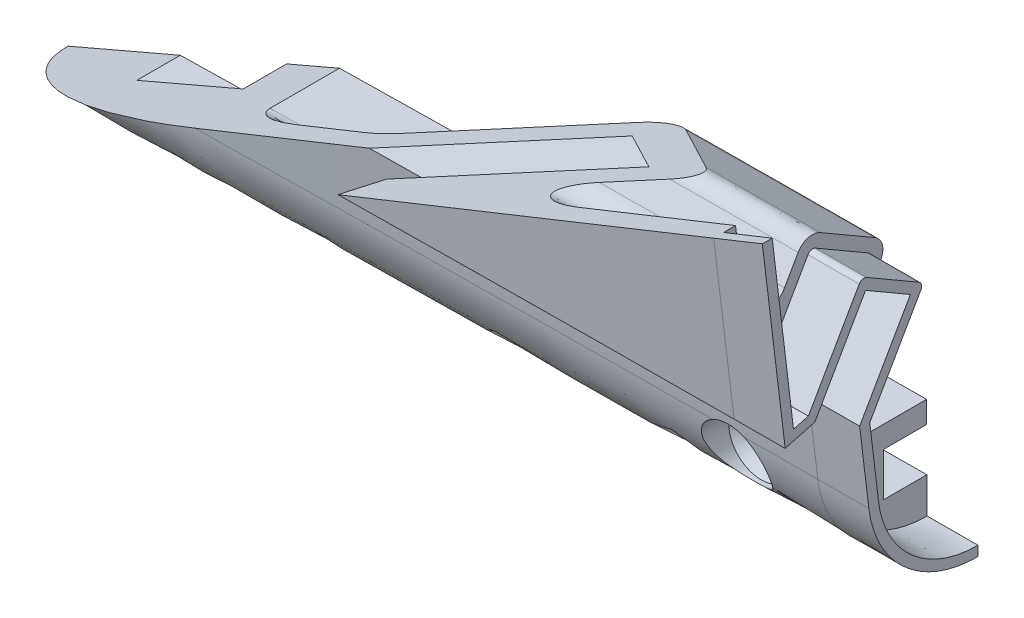
SolidWorks part; units mm, degrees
ref_plane "Front Plane" through (0, 0, 0) normal (0, 0, 1) x (1, 0, 0)
ref_plane "Top Plane" through (0, 0, 0) normal (0, 1, 0) x (1, 0, 0)
ref_plane "Right Plane" through (0, 0, 0) normal (1, 0, 0) x (0, 0, -1)
ref_plane "Plane3" through (-117.056, -3.871, 0) normal (0.9995, 0.0331, 0) x (0, 0, -1)
sketch "Sketch2" plane through (-117.056, -3.871, 0) normal (0.9995, 0.0331, 0) x (0, 0, -1)
  line L0 (-101.6, -41.1511) -> (-101.6, -45.9265)
  line L1 (-101.6, -41.1511) -> (-101.6, -45.9265)
  line L2 (-106.68, -45.9265) -> (-106.68, -50.6257)
  line L3 (-106.68, -45.9265) -> (-106.68, -50.6257)
  line L4 (-101.6, -50.6257) -> (-106.68, -50.6257)
  line L5 (-101.6, -50.6257) -> (-106.68, -50.6257)
  line L6 (-101.6, -50.6257) -> (-101.6, -56.1377)
  line L7 (-101.6, -50.6257) -> (-101.6, -56.1377)
  line L8 (-106.68, -45.9265) -> (-101.6, -45.9265)
  line L9 (-106.68, -45.9265) -> (-101.6, -45.9265)
  line L10 (-106.8705, -50.8162) -> (-108.9961, -53.9781) construction
  line L11 (-101.7905, -43.196) -> (-101.7905, -45.736)
  line L12 (-106.8705, -45.736) -> (-101.7905, -45.736)
  line L13 (-106.8705, -45.736) -> (-106.8705, -50.8162)
  line L14 (-101.7905, -50.8162) -> (-106.8705, -50.8162)
  line L15 (-101.7905, -50.8162) -> (-101.7905, -56.1377)
  line L16 (-101.7905, -43.196) -> (-101.6, -43.196)
  line L17 (-101.7905, -41.1511) -> (-101.7905, -45.736) construction
  line L18 (-120.8053, -33.0481) -> (-115.57, -36.0708)
  line L19 (-120.8053, -33.0481) -> (-115.57, -36.0708)
  line L20 (-109.601, -25.7318) -> (-114.8363, -22.709)
  line L21 (-109.601, -25.7318) -> (-114.8363, -22.709)
  line L22 (-114.8363, -22.709) -> (-120.8053, -33.0481)
  line L23 (-114.8363, -22.709) -> (-120.8053, -33.0481)
  line L24 (-115.57, -36.0708) -> (-109.601, -25.7318)
  line L25 (-115.57, -36.0708) -> (-109.601, -25.7318)
  line L26 (-115.57, -36.0708) -> (-114.523, -44.9291)
  line L28 (-118.1876, -34.5595) -> (-112.2186, -24.2204) construction
  line L29 (-114.6403, -39.5406) -> (-107.0838, -26.4518)
  line L30 (-107.7811, -23.8496) -> (-114.1162, -20.1918)
  line L31 (-116.7185, -20.8891) -> (-124.2749, -33.9778)
  line L33 (-106.1314, -24.8021) -> (-115.766, -19.2393) construction
  line L34 (-115.766, -19.2393) -> (-124.2749, -33.9778) construction
  line L35 (-114.6403, -39.5406) -> (-106.1314, -24.8021) construction
  line L36 (-124.2749, -33.9778) -> (-114.6403, -39.5406) construction
  line L37 (-112.9486, -36.6103) -> (-112.1701, -43.196)
  line L38 (-124.2749, -33.9778) -> (-128.0422, -2.1051)
  line L39 (-128.0422, -2.1051) -> (-132.6063, -0.4439)
  line L40 (-50.8, 0.7495) -> (-2184.4, 0.7495)
  line L41 (-125.822, 0.7495) -> (-133.442, 0.7495)
  line L42 (-122.1519, -30.3004) -> (-125.822, 0.7495)
  arc A0 (-114.523, -44.9291) -> (-101.7905, -56.1377) centre (-101.9108, -43.4383) ccw
  arc A2 (-114.1162, -20.1918) -> (-116.7185, -20.8891) centre (-115.0687, -21.8416) ccw
  arc A3 (-107.0838, -26.4518) -> (-107.7811, -23.8496) centre (-108.7336, -25.4993) ccw
  arc A4 (-133.442, 0.7495) -> (-132.6063, -0.4439) centre (-132.172, 0.7495) ccw
  point P41 (-133.442, 0.7495)
  dimension "D2" = 25.4
  dimension "D6" = 1.905
  dimension "D8" = 2.54
  dimension "D4" = 2.54
  dimension "D5" = 2.54
  dimension "D7" = 2.54
  dimension "D9" = 2.54
  dimension "D10" = 20
  dimension "D11" = 7.62
  dimension "D12" = 3.81
  dimension "D3" = 0.1905
sketch "Sketch3" plane through (0, 0, 101.6) normal (0, 0, 1) x (1, 0, 0)
  arc A0 (622.1039, -83.1998) -> (-622.1039, -83.1998) centre (0, -4954.4862) ccw construction
  arc A1 (622.1039, -83.1998) -> (-622.1039, -83.1998) centre (0, -4954.4862) ccw
sketch "Sketch4" plane through (-117.3306, 4.4304, 1117.6) normal (0.9995, 0.0331, 0) x (0, 0, -1)
  line L29 (1009.8189, -32.1556) -> (1003.4838, -28.4978) construction
  line L32 (1000.8815, -29.1951) -> (993.3251, -42.2838) construction
  line L35 (993.3251, -42.2838) -> (989.5578, -10.4111) construction
  line L50 (995.4481, -38.6064) -> (991.778, -7.5565) construction
  line L51 (1002.03, -44.3768) -> (1003.077, -53.235) construction
  line L52 (1015.8095, -59.1222) -> (1015.8095, -64.4437) construction
  line L53 (1015.8095, -59.1222) -> (1010.7295, -59.1222) construction
  line L54 (1010.7295, -54.042) -> (1010.7295, -59.1222) construction
  line L55 (1010.7295, -54.042) -> (1015.8095, -54.042) construction
  line L56 (1015.8095, -51.502) -> (1015.8095, -54.042) construction
  line L57 (1015.8095, -51.502) -> (1016, -51.502) construction
  line L58 (1004.6514, -44.9163) -> (1005.4299, -51.502) construction
  line L60 (1002.7637, -31.015) -> (996.7947, -41.3541) construction
  line L61 (1007.999, -34.0377) -> (1002.7637, -31.015) construction
  line L62 (1002.03, -44.3768) -> (1007.999, -34.0377) construction
  line L64 (991.5295, -5.4538) -> (988.9718, -5.4538)
  line L69 (1009.8189, -32.1556) -> (1003.4838, -28.4978)
  line L70 (1000.8815, -29.1951) -> (999.2724, -31.9822)
  line L71 (993.3251, -42.2838) -> (988.9718, -5.4538)
  line L74 (994.5502, -31.0104) -> (991.5295, -5.4538)
  line L75 (1002.03, -44.3768) -> (1003.077, -53.235)
  line L76 (1015.8095, -59.1222) -> (1015.8095, -64.4437)
  line L77 (1015.8095, -59.1222) -> (1010.7295, -59.1222)
  line L78 (1010.7295, -54.042) -> (1010.7295, -59.1222)
  line L79 (1010.7295, -54.042) -> (1015.8095, -54.042)
  line L80 (1015.8095, -51.502) -> (1015.8095, -54.042)
  line L81 (1015.8095, -51.502) -> (1007.6873, -51.502)
  line L82 (1004.7505, -45.7539) -> (1005.1649, -49.2601)
  line L84 (1002.7637, -31.015) -> (996.7947, -41.3541)
  line L85 (1007.999, -34.0377) -> (1002.7637, -31.015)
  line L86 (1002.03, -44.3768) -> (1007.999, -34.0377)
  line L87 (996.7947, -41.3541) -> (993.3251, -42.2838)
  line L88 (1005.0732, -44.1858) -> (1010.5162, -34.7578)
  arc A8 (1010.5162, -34.7578) -> (1009.8189, -32.1556) centre (1008.8664, -33.8053) ccw construction
  arc A9 (1003.4838, -28.4978) -> (1000.8815, -29.1951) centre (1002.5313, -30.1476) ccw construction
  arc A11 (1003.077, -53.235) -> (1015.8095, -64.4437) centre (1015.6892, -51.7443) ccw construction
  arc A12 (1010.5162, -34.7578) -> (1009.8189, -32.1556) centre (1008.8664, -33.8053) ccw
  arc A13 (1003.4838, -28.4978) -> (1000.8815, -29.1951) centre (1002.5313, -30.1476) ccw
  arc A15 (1003.077, -53.235) -> (1015.8095, -64.4437) centre (1015.6892, -51.7443) ccw
  arc A16 (1005.1649, -49.2601) -> (1007.6873, -51.502) centre (1007.6873, -48.962) ccw
  arc A17 (1004.7505, -45.7539) -> (1005.0732, -44.1858) centre (1007.2729, -45.4558) cw
  arc A18 (994.5502, -31.0104) -> (999.2724, -31.9822) centre (997.0727, -30.7122) ccw
  dimension "D2" = 2.54
  dimension "D1" = 36.83
sweep "Sweep3" add profiles "Sketch4" path "Sketch3"
sketch "Sketch5" plane through (0, 0, 101.7905) normal (0, 0, -1) x (-1, 0, 0)
  line L0 (211.6509, -4.1577) -> (0, -4954.4862) construction
  line L1 (0, -4954.4862) -> (22.6652, -1.2703) construction
  line L2 (117.0808, -1.0187) -> (0, -4954.4862) construction
  arc A1 (628.0925, -39.606) -> (-627.2635, -39.5001) centre (0, -4954.4862) ccw construction
  point P16 (117.0808, -1.0187)
ref_plane "Plane1" through (-211.4422, -9.0402, 0) normal (-0.9991, -0.0427, 0) x (0.0427, -0.9991, 0)
ref_plane "Plane2" through (-22.6706, -0.1037, 0) normal (1, 0.0046, 0) x (-0.0046, 1, 0)
other "SurfaceCut1"
other "SurfaceCut2"
sketch "Sketch8" plane through (-117.056, -3.871, 0) normal (0.9995, 0.0331, 0) x (0, 0, -1)
  line L0 (-106.8705, -50.8162) -> (-106.8705, -45.736)
  line L1 (-106.8705, -50.8162) -> (-106.8705, -45.736)
  line L2 (-106.8705, -48.2761) -> (-119.5705, -48.2761)
  line L3 (-119.5705, -48.2761) -> (-119.5705, -44.4661)
  line L4 (-119.5705, -44.4661) -> (-110.6805, -44.4661)
  line L5 (-110.6805, -44.4661) -> (-108.7755, -46.3711)
  line L6 (-108.7755, -46.3711) -> (-106.8705, -46.3711)
  line L7 (-119.5705, -48.2761) -> (-117.7248, -48.2761) construction
  dimension "D1" = 1.905
  dimension "D2" = 1.905
  dimension "D3" = 12.7
  dimension "D4" = 45
  dimension "D5" = 3.81
revolve "Cut-Revolve1" cut sketch "Sketch8" angle 360 about L7
sketch "Sketch9" plane through (0, 0, 106.8705) normal (0, 0, -1) x (-1, 0, 0)
  line L0 (198.0737, -52.2212) -> (197.8686, -57.297) construction
  line L1 (32.934, -48.3318) -> (32.8999, -53.4117) construction
  arc A1 (209.5755, -52.6994) -> (22.4502, -48.2726) centre (0, -4954.4862) ccw construction
  arc A2 (209.3585, -57.7748) -> (22.4269, -53.3526) centre (0, -4954.4862) ccw construction
  point P8 (197.9712, -54.7591)
  point P11 (0, -4954.4862)
  point P16 (115.4604, -52.1207)
  dimension "D1" = 82.55
  dimension "D2" = 82.55
sketch "Sketch10" plane through (0, 0, 106.8705) normal (0, 0, -1) x (-1, 0, 0)
  line L0 (32.934, -48.3318) -> (32.8999, -53.4117) construction
  point P0 (32.917, -50.8717)
  point P1 (197.9712, -54.7591)
pattern_sketch "Sketch-Pattern1" of "Cut-Revolve1" driven by "Sketch10"
sketch "Sketch12" plane through (0, 0, 101.7905) normal (0, 0, -1) x (-1, 0, 0)
  line L0 (22.4618, -45.7328) -> (0, -4954.4862) construction
  line L1 (0, -4954.4862) -> (16.4928, -45.7091) construction
  arc A1 (209.684, -50.1619) -> (22.4618, -45.7328) centre (0, -4954.4862) ccw construction
  arc A2 (22.4618, -45.7328) -> (16.4928, -45.7091) centre (0, -4954.4862) ccw
  dimension "D1" = 5.969
sketch "Sketch11" plane through (-22.6706, -0.1037, 0) normal (1, 0.0046, 0) x (0, 0, -1)
  line L0 (-127.4772, 0.4166) -> (-123.2949, -34.9658)
  line L1 (-123.2949, -34.9658) -> (-121.5584, -34.5006)
  line L2 (-121.5584, -34.5006) -> (-115.5722, -24.132)
  line L3 (-114.7047, -23.8996) -> (-108.5896, -27.4302)
  line L4 (-108.3571, -28.2976) -> (-114.3903, -38.7475)
  line L5 (-114.3903, -38.7475) -> (-113.3879, -47.2283)
  line L6 (-127.4931, 0.5508) -> (-123.2949, -34.9658) construction
  line L7 (-101.7905, -58.5707) -> (-101.7905, -57.4277)
  line L8 (-101.7905, -53.2494) -> (-101.7905, -58.5707) construction
  line L9 (-101.7905, -57.4277) -> (-101.8013, -57.4277)
  line L10 (-115.2547, -23.5821) -> (-108.0396, -27.7477) construction
  line L11 (-108.0396, -27.7477) -> (-114.3903, -38.7475) construction
  line L12 (-121.5584, -34.5006) -> (-115.2547, -23.5821) construction
  line L18 (-126.0705, 0.4166) -> (-128.6282, 0.4166)
  line L19 (-128.6282, 0.4166) -> (-124.2749, -36.4117)
  line L20 (-124.2749, -36.4117) -> (-120.8053, -35.4821)
  line L21 (-120.8053, -35.4821) -> (-114.8363, -25.1435)
  line L22 (-114.8363, -25.1435) -> (-109.601, -28.1661)
  line L23 (-109.601, -28.1661) -> (-115.57, -38.5047)
  line L24 (-115.57, -38.5047) -> (-114.523, -47.3625)
  line L25 (-101.7905, -58.5707) -> (-101.7905, -53.2494)
  line L26 (-101.7905, -53.2494) -> (-106.8705, -53.2494)
  line L27 (-106.8705, -53.2494) -> (-106.8705, -48.1694)
  line L28 (-106.8705, -48.1694) -> (-101.7905, -48.1694)
  line L29 (-101.7905, -48.1694) -> (-101.7905, -45.6295)
  line L30 (-101.7905, -45.6295) -> (-109.9127, -45.6295)
  line L31 (-112.4351, -43.3877) -> (-112.8495, -39.8818)
  line L32 (-112.5268, -38.3137) -> (-107.0838, -28.8861)
  line L33 (-107.781, -26.284) -> (-114.1162, -22.6264)
  line L34 (-116.7185, -23.3237) -> (-118.3276, -26.1106)
  line L35 (-123.0498, -25.1389) -> (-126.0705, 0.4166)
  line L36 (-127.4772, 0.4166) -> (-128.6282, 0.4166)
  line L37 (-128.6282, 0.4166) -> (-124.2749, -36.4117)
  line L38 (-124.2749, -36.4117) -> (-120.8053, -35.4821)
  line L39 (-120.8053, -35.4821) -> (-114.8363, -25.1435)
  line L40 (-114.8363, -25.1435) -> (-109.601, -28.1661)
  line L41 (-109.601, -28.1661) -> (-115.57, -38.5047)
  line L42 (-115.57, -38.5047) -> (-114.523, -47.3625)
  arc A0 (-108.5896, -27.4302) -> (-108.3571, -28.2976) centre (-108.9071, -27.9801) cw
  arc A1 (-115.5722, -24.132) -> (-114.7047, -23.8996) centre (-115.0222, -24.4495) cw
  arc A4 (-112.4351, -43.3877) -> (-109.9127, -45.6295) centre (-109.9127, -43.0896) ccw
  arc A5 (-112.5268, -38.3137) -> (-112.8495, -39.8818) centre (-110.3273, -39.5836) ccw
  arc A6 (-107.0838, -28.8861) -> (-107.781, -26.284) centre (-108.7335, -27.9337) ccw
  arc A7 (-114.1162, -22.6264) -> (-116.7185, -23.3237) centre (-115.0687, -24.2762) ccw
  spline S0 degree 1 poles (-113.3879, -47.2283) (-101.8013, -57.4277) knots 0 0 1 1 construction
  spline S1 degree 3 poles (-113.3879, -47.2283) (-113.3048, -47.9312) (-113.0054, -49.3311) (-111.9316, -51.9219) (-109.7159, -54.7453) (-106.0351, -56.9462) (-103.2019, -57.441) (-101.8013, -57.4277) knots 0 0 0 0 0.125 0.25 0.5 0.75 1 1 1 1
  spline S2 degree 3 poles (1806.7112, 500.6593) (415.3182, 185.4237) (-128.7728, 19.3055) (-114.2511, -48.8979) (-114.1523, -49.2753) (-113.8076, -50.3831) (-113.513, -51.0943) (-112.7943, -52.462) (-112.3662, -53.122) (-111.4114, -54.3345) (-110.8822, -54.8938) (-110.0099, -55.6614) (-109.7043, -55.9064) (-109.0766, -56.3638) (-108.7542, -56.5768) (-107.762, -57.1694) (-107.0674, -57.5033) (-105.9744, -57.9099) (-105.6018, -58.0293) (-104.8546, -58.2314) (-104.4782, -58.315) (-51.6561, -67.5542) (53.4105, 250.9973) (369.459, 1883.4824) knots -11.048432 -11.048432 -11.048432 -11.048432 0.0625 0.0625 0.125 0.125 0.25 0.25 0.375 0.375 0.5 0.5 0.5625 0.5625 0.625 0.625 0.75 0.75 0.8125 0.8125 0.875 0.875 9.519326 9.519326 9.519326 9.519326 only from (-114.523, -47.3625) to (-101.7905, -58.5707)
  spline S3 degree 3 poles (-966.8365, -555.2861) (-146.5253, 43.3444) (-110.7563, -19.4508) (-119.0219, -26.9033) (-119.2485, -27.051) (-119.7291, -27.2663) (-119.9898, -27.337) (-120.3827, -27.3799) (-120.5144, -27.384) (-120.779, -27.3716) (-120.9121, -27.3548) (-121.1705, -27.3014) (-121.297, -27.2648) (-121.5443, -27.1719) (-121.6661, -27.1149) (-121.896, -26.9844) (-122.0051, -26.9107) (-122.2115, -26.7465) (-122.3097, -26.6551) (-122.5785, -26.3621) (-122.7254, -26.141) (-131.5662, -6.8587) (104.7841, 84.3424) (817.0786, 315.6789) knots -5.03449 -5.03449 -5.03449 -5.03449 0.125 0.125 0.25 0.25 0.375 0.375 0.4375 0.4375 0.5 0.5 0.5625 0.5625 0.625 0.625 0.6875 0.6875 0.75 0.75 0.875 0.875 10.718854 10.718854 10.718854 10.718854 only from (-118.3276, -26.1106) to (-123.0498, -25.1389)
  spline S4 degree 3 poles (-114.523, -47.3625) (-114.4771, -47.7503) (-114.4136, -48.1349) (-114.2511, -48.8979) (-114.1523, -49.2753) (-113.8076, -50.3831) (-113.513, -51.0943) (-112.7943, -52.462) (-112.3662, -53.122) (-111.4114, -54.3345) (-110.8822, -54.8938) (-110.0099, -55.6614) (-109.7043, -55.9064) (-109.0766, -56.3638) (-108.7542, -56.5768) (-107.762, -57.1694) (-107.0674, -57.5033) (-105.9744, -57.9099) (-105.6018, -58.0293) (-104.8546, -58.2314) (-104.4782, -58.315) (-103.3407, -58.514) (-102.5713, -58.5781) (-101.7905, -58.5707) knots 0 0 0 0 0.0625 0.0625 0.125 0.125 0.25 0.25 0.375 0.375 0.5 0.5 0.5625 0.5625 0.625 0.625 0.75 0.75 0.8125 0.8125 0.875 0.875 1 1 1 1
  dimension "D3" = 0.635
  dimension "D1" = 0
  dimension "D2" = 1.143
sweep "Sweep4" add profiles "Sketch11" path "Sketch12"
sketch "Sketch14" plane through (-211.4422, -9.0402, 0) normal (-0.9991, -0.0427, 0) x (0, 0, 1)
  line L0 (113.0095, -42.7133) -> (113.9971, -34.3581)
  line L1 (113.9971, -34.3581) -> (107.5192, -23.138)
  line L2 (107.5192, -23.138) -> (115.3941, -18.5914)
  line L3 (115.3941, -18.5914) -> (121.8095, -29.7031)
  line L4 (121.8095, -29.7031) -> (122.9682, -30.0136)
  line L5 (122.9682, -30.0136) -> (127.1147, 5.0658)
  line L18 (128.6282, 4.8869) -> (126.0705, 4.8869)
  line L19 (126.0705, 4.8869) -> (123.0498, -20.6686)
  line L20 (118.3276, -21.6403) -> (116.7185, -18.8534)
  line L21 (114.1162, -18.1561) -> (107.7811, -21.8137)
  line L22 (107.0838, -24.4158) -> (112.5268, -33.8434)
  line L23 (112.8495, -35.4115) -> (112.4351, -38.9175)
  line L24 (109.9127, -41.1592) -> (101.7905, -41.1592)
  line L25 (101.7905, -41.1592) -> (101.7905, -43.6991)
  line L26 (101.7905, -43.6991) -> (106.8705, -43.6991)
  line L27 (106.8705, -43.6991) -> (106.8705, -48.7791)
  line L28 (106.8705, -48.7791) -> (101.7905, -48.7791)
  line L29 (101.7905, -48.7791) -> (101.7905, -54.1004)
  line L30 (114.523, -42.8922) -> (115.57, -34.0344)
  line L31 (115.57, -34.0344) -> (109.601, -23.6958)
  line L32 (109.601, -23.6958) -> (114.8363, -20.6732)
  line L33 (114.8363, -20.6732) -> (120.8053, -31.0118)
  line L34 (120.8053, -31.0118) -> (124.2749, -31.9414)
  line L35 (124.2749, -31.9414) -> (128.6282, 4.8869)
  line L36 (128.6282, 4.8869) -> (126.0705, 4.8869)
  line L37 (126.0705, 4.8869) -> (123.0498, -20.6686)
  line L38 (118.3276, -21.6403) -> (116.7185, -18.8534)
  line L39 (114.1162, -18.1561) -> (107.7811, -21.8137)
  line L40 (107.0838, -24.4158) -> (112.5268, -33.8434)
  line L41 (112.8495, -35.4115) -> (112.4351, -38.9175)
  line L42 (109.9127, -41.1592) -> (101.7905, -41.1592)
  line L43 (101.7905, -41.1592) -> (101.7905, -43.6991)
  line L44 (101.7905, -43.6991) -> (106.8705, -43.6991)
  line L45 (106.8705, -43.6991) -> (106.8705, -48.7791)
  line L46 (106.8705, -48.7791) -> (101.7905, -48.7791)
  line L47 (101.7905, -48.7791) -> (101.7905, -54.1004)
  line L48 (114.523, -42.8922) -> (115.57, -34.0344)
  line L49 (115.57, -34.0344) -> (109.601, -23.6958)
  line L50 (109.601, -23.6958) -> (114.8363, -20.6732)
  line L51 (114.8363, -20.6732) -> (120.8053, -31.0118)
  line L52 (120.8053, -31.0118) -> (124.2749, -31.9414)
  line L53 (124.2749, -31.9414) -> (128.6282, 4.8869)
  arc A4 (116.7185, -18.8534) -> (114.1162, -18.1561) centre (115.0687, -19.8059) ccw
  arc A5 (107.7811, -21.8137) -> (107.0838, -24.4158) centre (108.7335, -23.4634) ccw
  arc A6 (112.8495, -35.4115) -> (112.5268, -33.8434) centre (110.3273, -35.1133) ccw
  arc A7 (109.9127, -41.1592) -> (112.4351, -38.9175) centre (109.9127, -38.6193) ccw
  arc A8 (116.7185, -18.8534) -> (114.1162, -18.1561) centre (115.0687, -19.8059) ccw
  arc A9 (107.7811, -21.8137) -> (107.0838, -24.4158) centre (108.7335, -23.4634) ccw
  arc A10 (112.8495, -35.4115) -> (112.5268, -33.8434) centre (110.3273, -35.1133) ccw
  arc A11 (109.9127, -41.1592) -> (112.4351, -38.9175) centre (109.9127, -38.6193) ccw
  spline S0 degree 1 poles (101.8049, -52.5765) (113.0095, -42.7133) knots 0 0 1 1 construction
  spline S1 degree 3 poles (101.8049, -52.5765) (102.4893, -52.583) (103.8689, -52.4674) (106.4858, -51.7551) (109.4658, -49.9761) (112.0284, -46.7154) (112.8505, -44.0584) (113.0095, -42.7133) knots 0 0 0 0 0.125 0.25 0.5 0.75 1 1 1 1
  spline S2 degree 3 poles (-1420.2451, -2589.1907) (7.5348, 76.4537) (129.3579, -7.252) (122.7249, -21.671) (122.575, -21.8961) (122.2185, -22.2837) (122.0069, -22.4517) (121.6628, -22.6462) (121.5435, -22.702) (121.2955, -22.795) (121.1665, -22.8321) (120.908, -22.8851) (120.7774, -22.9014) (120.5134, -22.9137) (120.3791, -22.9094) (120.1163, -22.8803) (119.987, -22.8557) (119.7325, -22.7864) (119.6063, -22.7412) (119.2436, -22.578) (119.0214, -22.433) (93.7379, 0.421) (581.1886, 448.0858) (2362.312, 1968.4478) knots -7.286241 -7.286241 -7.286241 -7.286241 0.125 0.125 0.25 0.25 0.375 0.375 0.4375 0.4375 0.5 0.5 0.5625 0.5625 0.625 0.625 0.6875 0.6875 0.75 0.75 0.875 0.875 16.766809 16.766809 16.766809 16.766809 only from (123.0498, -20.6686) to (118.3276, -21.6403)
  spline S3 degree 3 poles (-288.3388, 2916.9987) (-102.777, 757.3692) (19.5454, -60.9671) (103.3479, -54.0254) (103.7348, -53.9753) (104.8774, -53.7738) (105.6202, -53.5717) (107.068, -53.0324) (107.777, -52.6914) (109.1008, -51.8981) (109.7227, -51.4442) (110.5948, -50.6762) (110.8766, -50.4042) (111.4099, -49.8396) (111.662, -49.5468) (112.3757, -48.6378) (112.795, -47.9912) (113.3369, -46.9586) (113.5026, -46.6041) (113.7979, -45.8886) (113.9285, -45.5258) (132.5439, 14.5864) (-288.4354, 203.7302) (-2703.1014, 979.8882) knots -13.349036 -13.349036 -13.349036 -13.349036 0.0625 0.0625 0.125 0.125 0.25 0.25 0.375 0.375 0.5 0.5 0.5625 0.5625 0.625 0.625 0.75 0.75 0.8125 0.8125 0.875 0.875 11.030088 11.030088 11.030088 11.030088 only from (101.7905, -54.1004) to (114.523, -42.8922)
  spline S4 degree 3 poles (123.0498, -20.6686) (123.0184, -20.9338) (122.9449, -21.1927) (122.7249, -21.671) (122.575, -21.8961) (122.2185, -22.2837) (122.0069, -22.4517) (121.6628, -22.6462) (121.5435, -22.702) (121.2955, -22.795) (121.1665, -22.8321) (120.908, -22.8851) (120.7774, -22.9014) (120.5134, -22.9137) (120.3791, -22.9094) (120.1163, -22.8803) (119.987, -22.8557) (119.7325, -22.7864) (119.6063, -22.7412) (119.2436, -22.578) (119.0214, -22.433) (118.6267, -22.0763) (118.4611, -21.8716) (118.3276, -21.6403) knots 0 0 0 0 0.125 0.125 0.25 0.25 0.375 0.375 0.4375 0.4375 0.5 0.5 0.5625 0.5625 0.625 0.625 0.6875 0.6875 0.75 0.75 0.875 0.875 1 1 1 1
  spline S5 degree 3 poles (101.7905, -54.1004) (102.1809, -54.1041) (102.5705, -54.0898) (103.3479, -54.0254) (103.7348, -53.9753) (104.8774, -53.7738) (105.6202, -53.5717) (107.068, -53.0324) (107.777, -52.6914) (109.1008, -51.8981) (109.7227, -51.4442) (110.5948, -50.6762) (110.8766, -50.4042) (111.4099, -49.8396) (111.662, -49.5468) (112.3757, -48.6378) (112.795, -47.9912) (113.3369, -46.9586) (113.5026, -46.6041) (113.7979, -45.8886) (113.9285, -45.5258) (114.2702, -44.4227) (114.4313, -43.6677) (114.523, -42.8922) knots 0 0 0 0 0.0625 0.0625 0.125 0.125 0.25 0.25 0.375 0.375 0.5 0.5 0.5625 0.5625 0.625 0.625 0.75 0.75 0.8125 0.8125 0.875 0.875 1 1 1 1
  dimension "D1" = 0
  dimension "D2" = 1.524
sketch "Sketch15" plane through (-211.4422, -9.0402, 0) normal (-0.9991, -0.0427, 0) x (0, 0, 1)
  line L0 (113.0095, -42.7133) -> (113.9971, -34.3581) construction
  line L1 (113.9971, -34.3581) -> (107.5192, -23.138) construction
  line L2 (107.5192, -23.138) -> (115.3941, -18.5914) construction
  line L3 (115.3941, -18.5914) -> (121.8095, -29.7031) construction
  line L4 (121.8095, -29.7031) -> (122.9682, -30.0136) construction
  line L5 (122.9682, -30.0136) -> (127.1147, 5.0658) construction
  line L6 (113.0095, -42.7133) -> (113.9724, -34.5675)
  line L7 (113.8917, -34.1755) -> (107.5192, -23.138)
  line L8 (107.5192, -23.138) -> (115.3941, -18.5914)
  line L9 (115.3941, -18.5914) -> (121.678, -29.4753)
  line L10 (122.0636, -29.7712) -> (122.2594, -29.8237)
  line L11 (123.0543, -29.2848) -> (127.0936, 4.8869)
  line L12 (101.7905, -48.7791) -> (101.7905, -54.1004) construction
  line L13 (101.7905, -48.7791) -> (101.7905, -52.5765)
  line L14 (101.8049, -52.5765) -> (101.7905, -52.5765)
  line L18 (124.2749, -31.9414) -> (128.6282, 4.8869)
  line L19 (128.6282, 4.8869) -> (126.0705, 4.8869)
  line L20 (126.0705, 4.8869) -> (123.0498, -20.6686)
  line L21 (118.3276, -21.6403) -> (116.7185, -18.8534)
  line L22 (114.1162, -18.1561) -> (107.7811, -21.8137)
  line L23 (107.0838, -24.4158) -> (112.5268, -33.8434)
  line L24 (112.8495, -35.4115) -> (112.4351, -38.9175)
  line L25 (109.9127, -41.1592) -> (101.7905, -41.1592)
  line L26 (101.7905, -41.1592) -> (101.7905, -43.6991)
  line L27 (101.7905, -43.6991) -> (106.8705, -43.6991)
  line L28 (106.8705, -43.6991) -> (106.8705, -48.7791)
  line L29 (106.8705, -48.7791) -> (101.7905, -48.7791)
  line L30 (101.7905, -48.7791) -> (101.7905, -54.1004)
  line L31 (114.523, -42.8922) -> (115.57, -34.0344)
  line L32 (115.57, -34.0344) -> (109.601, -23.6958)
  line L33 (109.601, -23.6958) -> (114.8363, -20.6732)
  line L34 (114.8363, -20.6732) -> (120.8053, -31.0118)
  line L35 (120.8053, -31.0118) -> (124.2749, -31.9414)
  line L37 (127.0936, 4.8869) -> (126.0705, 4.8869)
  line L38 (126.0705, 4.8869) -> (123.0498, -20.6686)
  line L39 (118.3276, -21.6403) -> (116.7185, -18.8534)
  line L40 (114.1162, -18.1561) -> (107.7811, -21.8137)
  line L41 (107.0838, -24.4158) -> (112.5268, -33.8434)
  line L42 (112.8495, -35.4115) -> (112.4351, -38.9175)
  line L43 (109.9127, -41.1592) -> (101.7905, -41.1592)
  line L44 (101.7905, -41.1592) -> (101.7905, -43.6991)
  line L45 (101.7905, -43.6991) -> (106.8705, -43.6991)
  line L46 (106.8705, -43.6991) -> (106.8705, -48.7791)
  line L47 (106.8705, -48.7791) -> (101.7905, -48.7791)
  arc A0 (113.9724, -34.5675) -> (113.8917, -34.1755) centre (113.3418, -34.493) ccw
  arc A1 (121.678, -29.4753) -> (122.0636, -29.7712) centre (122.2279, -29.1578) ccw
  arc A2 (122.2594, -29.8237) -> (123.0543, -29.2848) centre (122.4237, -29.2103) ccw
  arc A4 (116.7185, -18.8534) -> (114.1162, -18.1561) centre (115.0687, -19.8059) ccw
  arc A5 (107.7811, -21.8137) -> (107.0838, -24.4158) centre (108.7335, -23.4634) ccw
  arc A6 (112.8495, -35.4115) -> (112.5268, -33.8434) centre (110.3273, -35.1133) ccw
  arc A7 (109.9127, -41.1592) -> (112.4351, -38.9175) centre (109.9127, -38.6193) ccw
  arc A8 (116.7185, -18.8534) -> (114.1162, -18.1561) centre (115.0687, -19.8059) ccw
  arc A9 (107.7811, -21.8137) -> (107.0838, -24.4158) centre (108.7335, -23.4634) ccw
  arc A10 (112.8495, -35.4115) -> (112.5268, -33.8434) centre (110.3273, -35.1133) ccw
  arc A11 (109.9127, -41.1592) -> (112.4351, -38.9175) centre (109.9127, -38.6193) ccw
  spline S0 degree 3 poles (1969.6766, 654.3437) (8.5109, 56.766) (75.3403, -60.2329) (106.4858, -51.7551) (109.4658, -49.9761) (134.2797, -18.4018) (-16.091, 107.1074) (-926.156, -1745.3361) knots -5.450838 -5.450838 -5.450838 -5.450838 0.125 0.25 0.5 0.75 7.512309 7.512309 7.512309 7.512309 only from (101.8049, -52.5765) to (113.0095, -42.7133) construction
  spline S1 degree 3 poles (101.8049, -52.5765) (102.4893, -52.583) (103.8689, -52.4674) (106.4858, -51.7551) (109.4658, -49.9761) (112.0284, -46.7154) (112.8505, -44.0584) (113.0095, -42.7133) knots 0 0 0 0 0.125 0.25 0.5 0.75 1 1 1 1
  spline S2 degree 3 poles (-1420.2451, -2589.1907) (7.5348, 76.4537) (129.3579, -7.252) (122.7249, -21.671) (122.575, -21.8961) (122.2185, -22.2837) (122.0069, -22.4517) (121.6628, -22.6462) (121.5435, -22.702) (121.2955, -22.795) (121.1665, -22.8321) (120.908, -22.8851) (120.7774, -22.9014) (120.5134, -22.9137) (120.3791, -22.9094) (120.1163, -22.8803) (119.987, -22.8557) (119.7325, -22.7864) (119.6063, -22.7412) (119.2436, -22.578) (119.0214, -22.433) (93.7379, 0.421) (581.1886, 448.0858) (2362.312, 1968.4478) knots -7.286241 -7.286241 -7.286241 -7.286241 0.125 0.125 0.25 0.25 0.375 0.375 0.4375 0.4375 0.5 0.5 0.5625 0.5625 0.625 0.625 0.6875 0.6875 0.75 0.75 0.875 0.875 16.766809 16.766809 16.766809 16.766809 only from (123.0498, -20.6686) to (118.3276, -21.6403)
  spline S3 degree 3 poles (-93.3253, 926.6784) (-10.5613, 232.0775) (53.1389, -58.1844) (103.3479, -54.0254) (103.7348, -53.9753) (104.8774, -53.7738) (105.6202, -53.5717) (107.068, -53.0324) (107.777, -52.6914) (109.1008, -51.8981) (109.7227, -51.4442) (110.5948, -50.6762) (110.8766, -50.4042) (111.4099, -49.8396) (111.662, -49.5468) (112.3757, -48.6378) (112.795, -47.9912) (113.3369, -46.9586) (113.5026, -46.6041) (113.7979, -45.8886) (113.9285, -45.5258) (125.9187, -6.8076) (-43.2917, 84.8615) (-804.6708, 350.8867) knots -7.947776 -7.947776 -7.947776 -7.947776 0.0625 0.0625 0.125 0.125 0.25 0.25 0.375 0.375 0.5 0.5 0.5625 0.5625 0.625 0.625 0.75 0.75 0.8125 0.8125 0.875 0.875 7.39364 7.39364 7.39364 7.39364 only from (101.7905, -54.1004) to (114.523, -42.8922)
  spline S4 degree 3 poles (123.0498, -20.6686) (123.0184, -20.9338) (122.9449, -21.1927) (122.7249, -21.671) (122.575, -21.8961) (122.2185, -22.2837) (122.0069, -22.4517) (121.6628, -22.6462) (121.5435, -22.702) (121.2955, -22.795) (121.1665, -22.8321) (120.908, -22.8851) (120.7774, -22.9014) (120.5134, -22.9137) (120.3791, -22.9094) (120.1163, -22.8803) (119.987, -22.8557) (119.7325, -22.7864) (119.6063, -22.7412) (119.2436, -22.578) (119.0214, -22.433) (118.6267, -22.0763) (118.4611, -21.8716) (118.3276, -21.6403) knots 0 0 0 0 0.125 0.125 0.25 0.25 0.375 0.375 0.4375 0.4375 0.5 0.5 0.5625 0.5625 0.625 0.625 0.6875 0.6875 0.75 0.75 0.875 0.875 1 1 1 1
  dimension "D2" = 0.635
  dimension "D1" = 0
sketch "Sketch16" plane through (0, 0, 101.7905) normal (0, 0, -1) x (-1, 0, 0)
  arc A0 (215.6474, -50.4205) -> (209.684, -50.1619) centre (0, -4954.4862) ccw
  arc A1 (209.684, -50.1619) -> (22.4618, -45.7328) centre (0, -4954.4862) ccw construction
  dimension "D1" = 5.969
sweep "Sweep5" add profiles "Sketch15" path "Sketch16"
ref_plane "Plane4" through (2.6726, -6.2214, 0) normal (0.3947, -0.9188, 0) x (-0.9188, -0.3947, 0)
other "SurfaceCut3"
